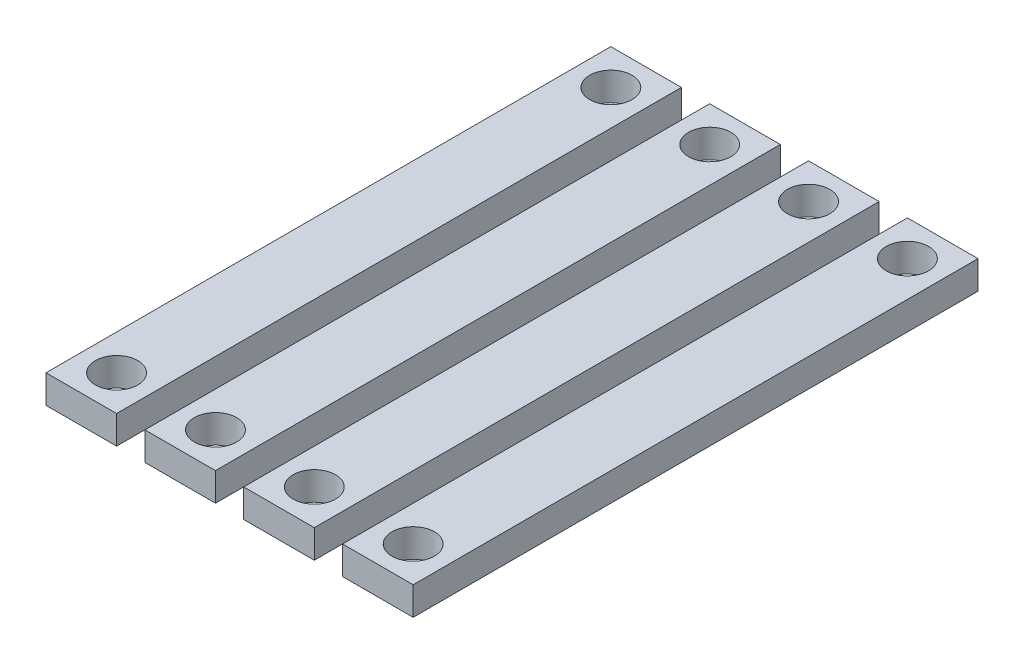
SolidWorks part; units mm, degrees
ref_plane "前视基准面" through (0, 0, 0) normal (0, 0, 1) x (1, 0, 0)
ref_plane "上视基准面" through (0, 0, 0) normal (0, 1, 0) x (1, 0, 0)
ref_plane "右视基准面" through (0, 0, 0) normal (1, 0, 0) x (0, 0, -1)
other "Configuration Table"
sketch "草图1" plane through (0, 0, 0) normal (0, 1, 0) x (1, 0, 0)
  line L1 (0, 0) -> (5, 0)
  line L2 (0, 0) -> (0, -40)
  line L3 (0, -40) -> (5, -40)
  line L4 (5, 0) -> (5, -40)
  circle A6 centre (2.5, -2.5) radius 1.5
  circle A10 centre (2.5, -37.5) radius 1.5
  point P8 (2.5, 0)
  dimension "D29" = 40
  dimension "D3" = 3
  dimension "D1" = 5
  dimension "D4" = 2.5
  dimension "D5" = 2.5
extrude "凸台-拉伸1" add sketch "草图1" along normal blind 2
pattern_linear "阵列(线性)2" count 4 spacing 7 along (1, 0, 0) of "凸台-拉伸1"
